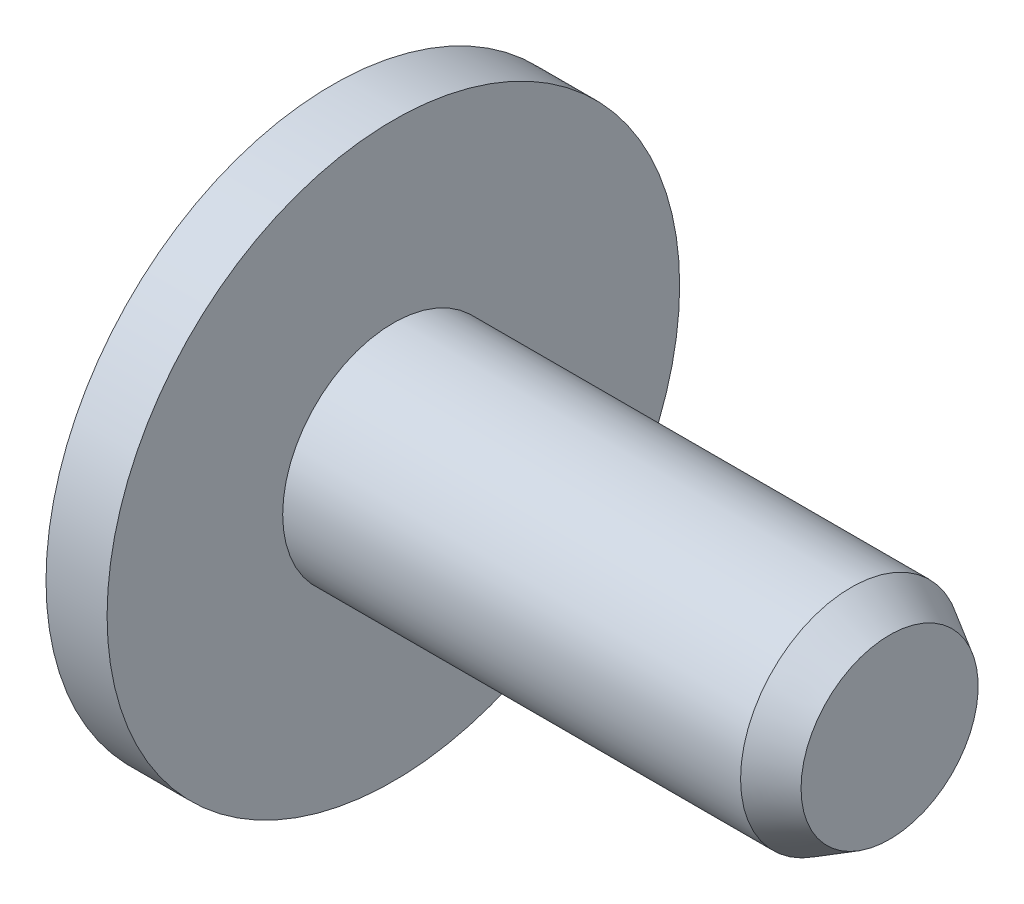
SolidWorks part; units mm, degrees
ref_plane "Front" through (0, 0, 0) normal (0, 0, 1) x (1, 0, 0)
ref_plane "Top" through (0, 0, 0) normal (0, 1, 0) x (1, 0, 0)
ref_plane "Right" through (0, 0, 0) normal (1, 0, 0) x (0, 0, -1)
sketch "Sketch1" plane through (0, 0, 0) normal (0, 0, 1) x (1, 0, 0)
  line L0 (0, 3.75) -> (0, 1.45)
  line L1 (0, 1.45) -> (6.5, 1.45)
  line L2 (6.5, 1.45) -> (6.5, 0)
  line L3 (0, 3.75) -> (-0.8, 3.75)
  line L4 (-0.8, 3.75) -> (-0.8, 3.0623)
  line L5 (-2.35, 0) -> (-2.35, -1.3041) construction
  line L7 (-6.4783, 0) -> (12.5724, 0) construction
  line L8 (-2.35, 0) -> (6.5, 0)
  arc A0 (-0.8, 3.0623) -> (-2.35, 0) centre (1.45, 0) ccw
  dimension "rf" = 3.8
  dimension "k" = 2.35
  dimension "dk" = 7.5
  dimension "c" = 0.8
  dimension "d" = 2.9
  dimension "l" = 6.5
revolve "Revolve1" add sketch "Sketch1" angle 360 about L7
cosmetic thread "ThreadCosmetic" [suppressed] parameters "D2"=1.4
chamfer "Chamfer1" distance 0.29 angle 60 1 edges at (6.5, 0, 1.45)
sketch "Sketch9" plane through (0, 0, 0) normal (0, 0, 1) x (1, 0, 0)
  line L0 (0.096, 0.7) -> (0.4811, 0.7)
  line L1 (0.4811, 0.7) -> (0.0481, 1.45)
  line L2 (0.096, 0.7) -> (0.529, 1.45)
  line L3 (0.0481, 1.45) -> (0.0481, 1.7)
  line L4 (0.529, 1.45) -> (0.529, 1.7)
  line L5 (0.0481, 1.7) -> (0.529, 1.7)
  line L6 (0.2886, 0.7) -> (0.2886, 0) construction
  line L7 (0, 0) -> (7.3035, 0) construction
  line L8 (0, -1.45) -> (0, 1.45) construction
  line L10 (0, -3.75) -> (0, 3.75) construction
  line L11 (5.9977, 1.45) -> (0, 1.45) construction
  dimension "D2" = 60
  dimension "D3" = 0.25
  dimension "threadstart" = 0.2886
  dimension "minordia" = 1.4
  dimension "advance" = 0.4809
revolve "ThreadSchematic" [suppressed] cut sketch "Sketch9" angle 360 about L7
pattern_linear "ThdSchPat" [suppressed] count 14 spacing 0.4809 along (1, 0, 0)
sketch "Sketch2" plane through (0, 0, 0) normal (0, 0, 1) x (1, 0, 0)
  line L0 (6.5, 1.45) -> (6.5, 0) construction
  line L1 (6.5, 0) -> (6.5, 1.0614) construction
  line L2 (0, 0) -> (8.4194, 0) construction
  line L5 (6.2098, -0.4431) -> (3.9, -1.45)
  line L7 (3.9, -1.45) -> (3.9, -1.65)
  line L8 (3.9, -1.65) -> (6.7, -1.65)
  line L9 (6.7, -1.65) -> (6.7, 0)
  line L10 (6.7, 0) -> (6.5, 0)
  arc A0 (6.2098, -0.4431) -> (6.5, 0) centre (6.0167, 0) ccw
  point P6 (0, -1.45)
  dimension "D1" = 0.4833
  dimension "yr" = 2.6
  dimension "D2" = 0.2
  dimension "D3" = 0.2
revolve "EndRound" [suppressed] cut sketch "Sketch2" angle 360 about L2
sketch "Sketch8" plane through (0, 0, 0) normal (0, 0, 1) x (1, 0, 0)
  line L0 (6.5, 0) -> (6.7, 0)
  line L1 (-6.4783, 0) -> (12.5724, 0) construction
  line L2 (6.7, 0) -> (6.7, -1.65)
  line L3 (6.7, -1.65) -> (3.9, -1.65)
  line L4 (3.9, -1.65) -> (3.9, -1.45)
  line L6 (3.9, -1.45) -> (6.5, 0)
  line L7 (0, 0) -> (9.5575, 0) construction
  line L8 (0, -1.45) -> (11.5982, -1.45) construction
  dimension "yc" = 2.6
  dimension "D2" = 0.2
  dimension "D3" = 0.2
revolve "EndCone" [suppressed] cut sketch "Sketch8" angle 360 about L7
ref_plane "Plane1" through (-2.35, 0, 0) normal (1, 0, 0) x (0, 0, -1)
sketch "Sketch4" plane through (-2.35, 0, 0) normal (1, 0, 0) x (0, 0, -1)
  line L0 (0.3, 1.5) -> (-0.3, 1.5)
  line L1 (-0.3, 1.5) -> (-0.3, 0.3)
  line L2 (-0.3, 0.3) -> (-1.5, 0.3)
  line L3 (-1.5, 0.3) -> (-1.5, -0.3)
  line L4 (-1.5, -0.3) -> (-0.3, -0.3)
  line L5 (-0.3, -0.3) -> (-0.3, -1.5)
  line L6 (-0.3, -1.5) -> (0.3, -1.5)
  line L7 (0.3, -1.5) -> (0.3, -0.3)
  line L8 (0.3, -0.3) -> (1.5, -0.3)
  line L9 (1.5, -0.3) -> (1.5, 0.3)
  line L10 (1.5, 0.3) -> (0.3, 0.3)
  line L11 (0.3, 0.3) -> (0.3, 1.5)
  line L12 (1.5, 0) -> (-1.5, 0) construction
  dimension "m" = 3
  dimension "D2" = 0.6
extrude "Cut-Extrude1" cut sketch "Sketch4" along normal blind 1.58
draft "Draft1" type of draft neutral plane draft angle 35 neutral plane "Plane1" faces to draft 4 face at (-1.4025, 0, -1.5) face at (-1.4025, -1.5, 0) face at (-1.4025, 0, 1.5) face at (-1.4025, 1.5, 0) neutral plane through (-2.35, 0, 0) neutral plane normal (1, 0, 0) reverse direction yes parameters "D1"=35
draft "Draft2" type of draft neutral plane draft angle 8 neutral plane "Plane1" faces to draft 8 face at (-1.5002, 0.5815, -0.3) face at (-1.5002, 0.3, -0.5815) face at (-1.5002, -0.3, -0.5815) face at (-1.5002, -0.5815, -0.3) face at (-1.5002, -0.5815, 0.3) face at (-1.5002, -0.3, 0.5815) face at (-1.5002, 0.3, 0.5815) face at (-1.5002, 0.5815, 0.3) neutral plane through (-2.35, 0, 0) neutral plane normal (1, 0, 0) reverse direction yes parameters "D1"=8
fillet "Fillet1" radius 0.25 4 edges at (-1.5484, -0.1873, -0.1873) (-1.5484, -0.1873, 0.1873) (-1.5484, 0.1873, 0.1873) (-1.5484, 0.1873, -0.1873)
sketch "Sketch7" plane through (-2.35, 0, 0) normal (1, 0, 0) x (0, 0, -1)
  line L0 (-0.265, 1.3259) -> (-1.3259, 1.3259) construction
  line L1 (-1.3259, 1.3259) -> (-1.3259, 0.265) construction
  line L2 (0, 0) -> (-1.3259, 1.3259) construction
  line L3 (-0.0779, 0.3255) -> (-1.3259, 1.3259)
  line L4 (-1.3259, 1.3259) -> (-0.3255, 0.0779)
  line L5 (-0.3255, 0.0779) -> (-0.3255, 0)
  line L6 (-0.0779, 0.3255) -> (0, 0.3255)
  line L7 (0.0779, 0.3255) -> (0, 0.3255)
  line L8 (1.3259, 1.3259) -> (0.0779, 0.3255)
  line L9 (0.3255, 0.0779) -> (1.3259, 1.3259)
  line L10 (0.3255, 0.0779) -> (0.3255, 0)
  line L11 (0.3255, -0.0779) -> (0.3255, 0)
  line L12 (1.3259, -1.3259) -> (0.3255, -0.0779)
  line L13 (0.0779, -0.3255) -> (1.3259, -1.3259)
  line L14 (0.0779, -0.3255) -> (0, -0.3255)
  line L15 (-0.0779, -0.3255) -> (0, -0.3255)
  line L16 (-1.3259, -1.3259) -> (-0.0779, -0.3255)
  line L17 (-0.3255, -0.0779) -> (-1.3259, -1.3259)
  line L18 (-0.3255, -0.0779) -> (-0.3255, 0)
extrude "TypeZ" [suppressed] cut sketch "Sketch7" along normal blind 0.316 draft 2
equation "\"minordia@Sketch9\" = \"D2@ThreadCosmetic\""
equation "\"D1@Chamfer1\" = \"d@Sketch1\" / 10"
equation "\"D1@Sketch2\" = \"d@Sketch1\" / 6"
equation "\"D2@Sketch4\" = \"m@Sketch4\" / 5"
equation "\"D1@TypeZ\" = \"depth@Cut-Extrude1\" * 0.2"
equation "\"D1@Fillet1\" =\"m@Sketch4\" /12"
equation "\"threadstart@Sketch9\" = \"advance@Sketch9\" * 0.6"
equation "\"D1@ThdSchPat\" = int((\"l@Sketch1\"/\"advance@Sketch9\") + 0.999)"
equation "\"D3@ThdSchPat\" = \"advance@Sketch9\""
